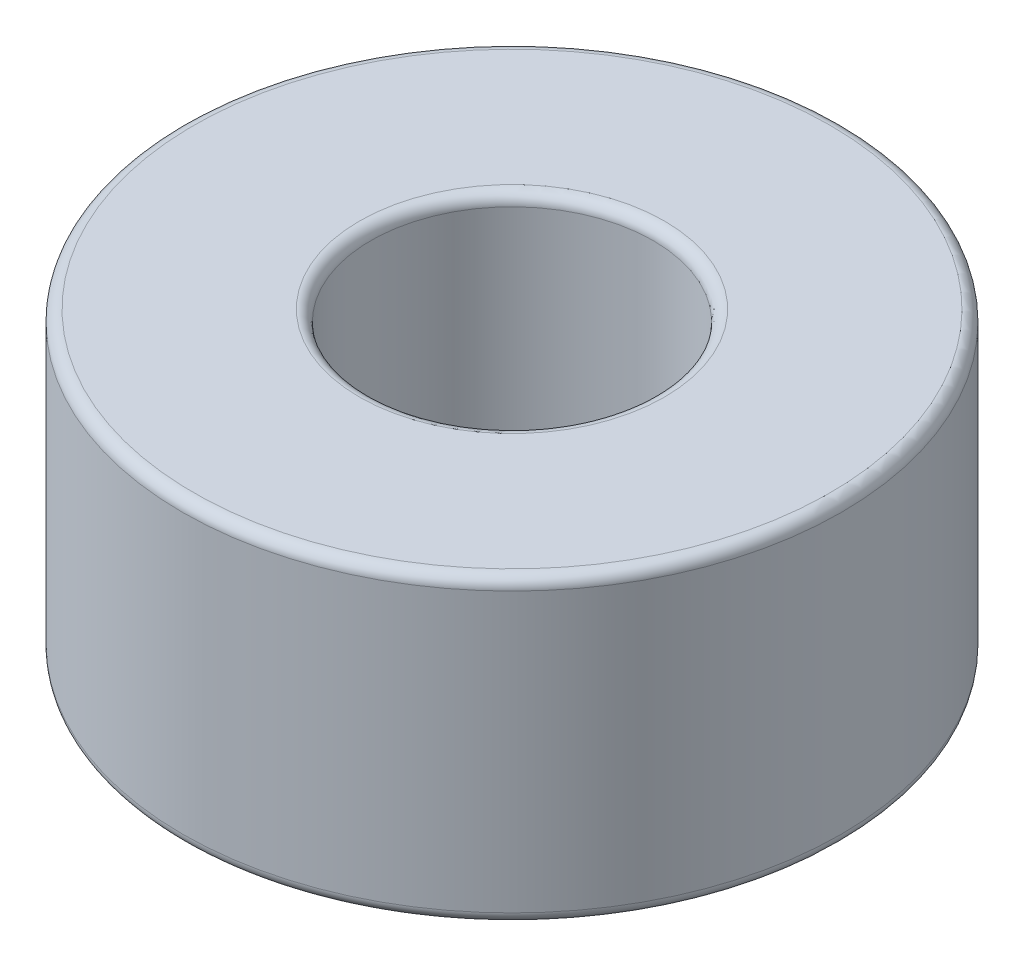
SolidWorks part; units mm, degrees
ref_plane "Płaszczyzna przednia" through (0, 0, 0) normal (0, 0, 1) x (1, 0, 0)
ref_plane "Płaszczyzna górna" through (0, 0, 0) normal (0, 1, 0) x (1, 0, 0)
ref_plane "Płaszczyzna prawa" through (0, 0, 0) normal (1, 0, 0) x (0, 0, -1)
sketch "Szkic1" plane through (0, 0, 0) normal (0, 0, 1) x (1, 0, 0)
  line L0 (0, 0) -> (0, 16) construction
  line L1 (-17.5, 15.4) -> (-17.5, 0.6)
  line L2 (-7.5, 15.4) -> (-7.5, 0.6)
  line L3 (-16.9, 16) -> (-8.1, 16)
  line L4 (-16.9, 0) -> (-8.1, 0)
  arc A0 (-17.5, 0.6) -> (-16.9, 0) centre (-16.9, 0.6) ccw
  arc A1 (-17.5, 15.4) -> (-16.9, 16) centre (-16.9, 15.4) cw
  arc A2 (-7.5, 15.4) -> (-8.1, 16) centre (-8.1, 15.4) ccw
  arc A3 (-7.5, 0.6) -> (-8.1, 0) centre (-8.1, 0.6) cw
  point P9 (-17.5, 0)
  point P12 (-17.5, 16)
  dimension "D4" = 0.6
  dimension "D1" = 16
  dimension "D2" = 17.5
  dimension "D3" = 7.5
revolve "Obrót1" add sketch "Szkic1" angle 360 about L0
